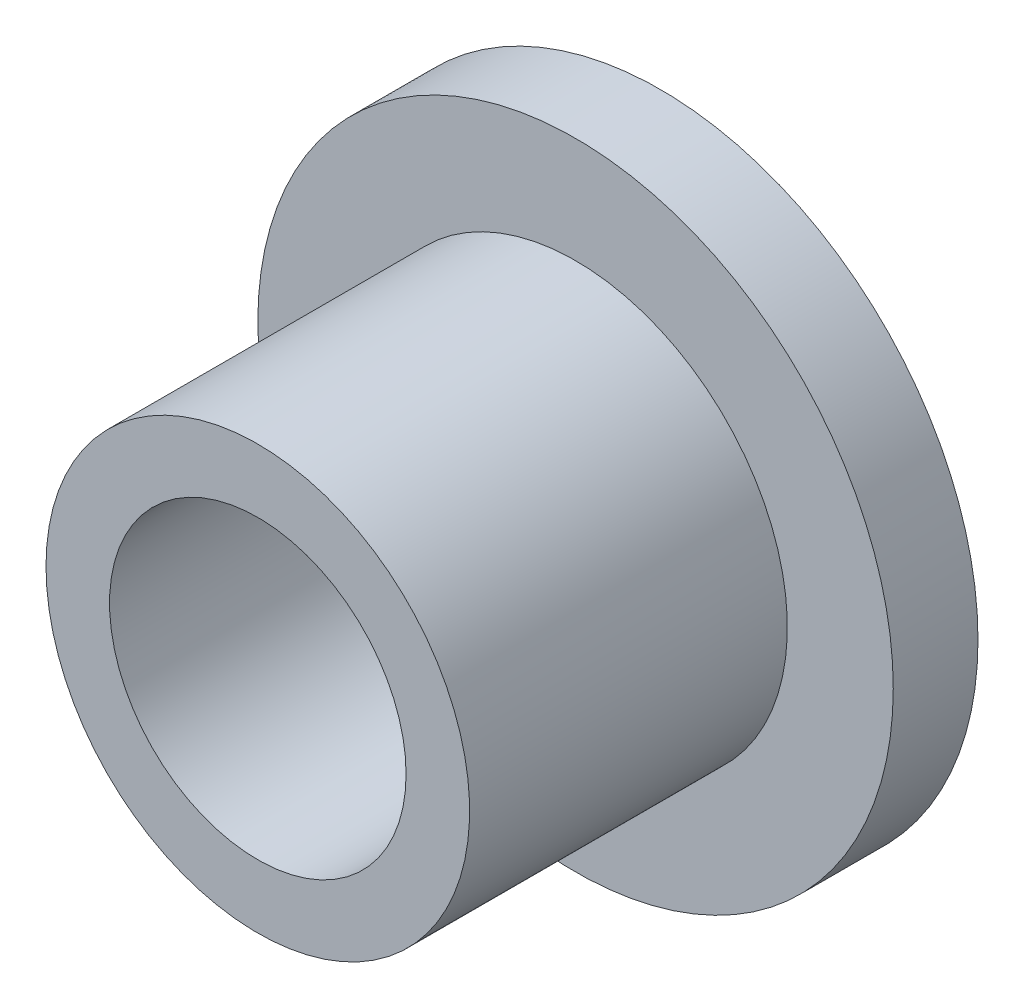
SolidWorks part; units mm, degrees
ref_plane "Front Plane" through (0, 0, 0) normal (0, 0, 1) x (1, 0, 0)
ref_plane "Top Plane" through (0, 0, 0) normal (0, 1, 0) x (1, 0, 0)
ref_plane "Right Plane" through (0, 0, 0) normal (1, 0, 0) x (0, 0, -1)
sketch "Sketch1" plane through (0, 0, 0) normal (0, 0, 1) x (1, 0, 0)
  circle A0 centre (0, 0) radius 19.05
extrude "Boss-Extrude1" add sketch "Sketch1" against normal blind 5.08
sketch "Sketch2" plane through (0, 0, 0) normal (0, 0, 1) x (1, 0, 0)
  circle A0 centre (0, 0) radius 12.7
extrude "Boss-Extrude2" add sketch "Sketch2" along normal blind 19.05
sketch "Sketch3" plane through (0, 0, 19.05) normal (0, 0, 1) x (1, 0, 0)
  circle A0 centre (0, 0) radius 8.89
extrude "Cut-Extrude1" cut sketch "Sketch3" against normal up to next
